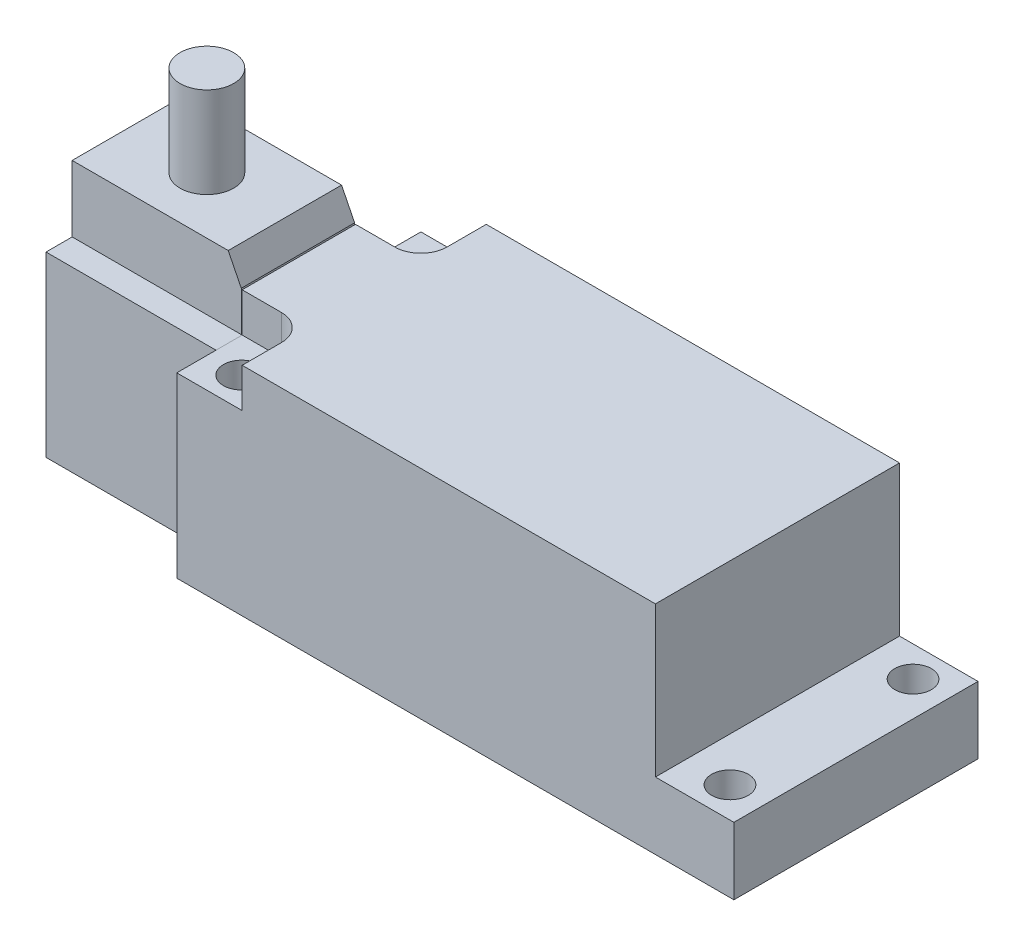
SolidWorks part; units mm, degrees
ref_plane "Front" through (0, 0, 0) normal (0, 0, 1) x (1, 0, 0)
ref_plane "Top" through (0, 0, 0) normal (0, 1, 0) x (1, 0, 0)
ref_plane "Right" through (0, 0, 0) normal (1, 0, 0) x (0, 0, -1)
sketch "Sketch1" plane through (0, 0, 0) normal (0, 1, 0) x (1, 0, 0)
  line L0 (0, 0) -> (63.9, 0) construction
  line L1 (0, -14) -> (63.9, -14)
  line L2 (0, -14) -> (0, 14)
  line L3 (0, 14) -> (63.9, 14)
  line L4 (63.9, -14) -> (63.9, 14)
  line L5 (31.95, 14) -> (31.95, -14) construction
  line L6 (3.95, -10.5) -> (59.95, 10.5) construction
  line L7 (3.95, -10.5) -> (59.95, -10.5) construction
  line L8 (3.95, -10.5) -> (3.95, 10.5) construction
  line L9 (3.95, 10.5) -> (59.95, 10.5) construction
  line L10 (59.95, -10.5) -> (59.95, 10.5) construction
  dimension "D1" = 28
  dimension "D2" = 63.9
  dimension "D3" = 21
  dimension "D4" = 56
extrude "Extrude1" add sketch "Sketch1" along normal blind 24.9
sketch "Sketch2" plane through (0, 0, 14) normal (0, 0, 1) x (1, 0, 0)
  line L1 (63.9, 24.9) -> (54.9, 24.9)
  line L2 (63.9, 24.9) -> (63.9, 7.7)
  line L3 (63.9, 7.7) -> (54.9, 7.7)
  line L4 (54.9, 24.9) -> (54.9, 7.7)
  dimension "D1" = 9
  dimension "D2" = 17.2
extrude "Cut-Extrude1" cut sketch "Sketch2" against normal through all
sketch "Sketch3" plane through (0, 24.9, 0) normal (0, 1, 0) x (-1, 0, 0)
  line L0 (0, 0) -> (-54.9, 0) construction
  line L1 (0, -14) -> (0, 14) construction
  line L2 (-54.9, -14) -> (-54.9, 14) construction
  line L3 (-7.5, -14) -> (-7.5, -9.5)
  line L4 (0, 14) -> (-7.5, 14)
  line L5 (0, 14) -> (0, 6.5)
  line L6 (0, 6.5) -> (-4.5, 6.5)
  line L7 (-7.5, 14) -> (-7.5, 9.5)
  line L8 (0, -6.5) -> (-4.5, -6.5)
  line L9 (0, -14) -> (0, -6.5)
  line L10 (0, -14) -> (-7.5, -14)
  arc A0 (-4.5, 6.5) -> (-7.5, 9.5) centre (-4.5, 9.5) cw
  arc A1 (-4.5, -6.5) -> (-7.5, -9.5) centre (-4.5, -9.5) ccw
  dimension "D2" = 3
  dimension "D1" = 7.5
extrude "Cut-Extrude2" cut sketch "Sketch3" against normal blind 4.5
sketch "Sketch5" plane through (0, 0, 0) normal (0, -1, 0) x (1, 0, 0)
  point P0 (59.95, 10.5)
  point P1 (59.95, -10.5)
  point P3 (3.95, -10.5)
  point P5 (3.95, 10.5)
hole_wizard "M5x0.8 Tapped Hole4" positions "3DSketch6" profile "Sketch10" tap size "M5x0.8" standard "Ansi Metric" end condition through all
sketch3d "3DSketch6"
  point P0 (3.95, 0, 10.5)
  point P2 (3.95, 0, -10.5)
  point P4 (59.95, 0, 10.5)
  point P6 (59.95, 0, -10.5)
cosmetic thread "Hole Thread12" parameters "D2"=5
sketch "Sketch10" plane through (3.95, 0, 10.5) normal (1, 0, 0) x (0, 0, -1)
  line L0 (0, 0) -> (0, 24.9)
  line L1 (0, 24.9) -> (2.1, 24.9)
  line L2 (2.1, 24.9) -> (2.1, 0)
  line L5 (2.1, 0) -> (0, 0)
  line L11 (0, -6.35) -> (0, 107.95) construction
  dimension "Thru Tap Drill Dia." = 4.2
  dimension "Thru Tap Drill Depth" = 24.9
cosmetic thread "Hole Thread13" parameters "D2"=5
cosmetic thread "Hole Thread14" parameters "D2"=5
cosmetic thread "Hole Thread15" parameters "D2"=5
sketch "Sketch11" plane through (0, 0, 0) normal (0, -1, 0) x (1, 0, 0)
  line L1 (-19.5, 9.5) -> (0, 9.5)
  line L2 (-19.5, 9.5) -> (-19.5, -9.5)
  line L3 (-19.5, -9.5) -> (0, -9.5)
  line L4 (0, 9.5) -> (0, -9.5)
  dimension "D1" = 19
  dimension "D2" = 19.5
extrude "Extrude2" add sketch "Sketch11" against normal blind 20.4 separate body
sketch "Sketch12" plane through (0, 20.4, 0) normal (0, 1, 0) x (-1, 0, 0)
  line L0 (0, -6.5) -> (0, 6.5)
  line L1 (0.1, 6.5) -> (19.5, 6.5)
  line L2 (19.5, 9.5) -> (19.5, -9.5) construction
  line L3 (19.5, 6.5) -> (19.5, -6.5)
  line L4 (19.5, -6.5) -> (0.1, -6.5)
  line L5 (0.1, -6.5) -> (0.1, 6.5)
  line M7 (19.5, -9.5) -> (19.5, 9.5)
extrude "Extrude4" add sketch "Sketch12" along normal blind 7.6 contours L5 L4 L1 M7
chamfer "Chamfer1" distance 1.5 distance2 3 1 edges at (-0.1, 28, 0)
sketch "Sketch13" plane through (0, 28, 0) normal (0, 1, 0) x (-1, 0, 0)
  circle A0 centre (10.55, 0) radius 3.075
extrude "Extrude5" add sketch "Sketch13" along normal blind 10.4
